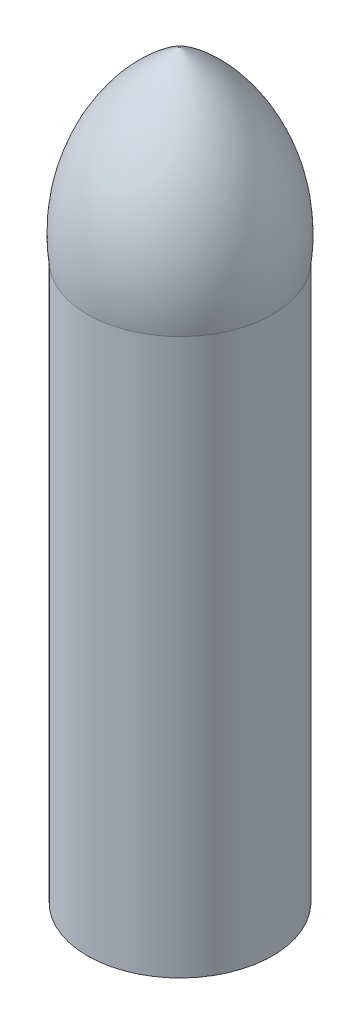
SolidWorks part; units mm, degrees
ref_plane "Front Plane" through (0, 0, 0) normal (0, 0, 1) x (1, 0, 0)
ref_plane "Top Plane" through (0, 0, 0) normal (0, 1, 0) x (1, 0, 0)
ref_plane "Right Plane" through (0, 0, 0) normal (1, 0, 0) x (0, 0, -1)
sketch "Sketch1" plane through (0, 0, 0) normal (0, 0, 1) x (1, 0, 0)
  line L0 (0, 0) -> (0, 100)
  line L1 (0, 0) -> (50, 0)
  arc A0 (0, 100) -> (50, 0) centre (-49.162, 12.919) cw
  dimension "D1" = 100
  dimension "D2" = 50
revolve "Revolve1" add sketch "Sketch1" angle 360 about L0
sketch "Sketch2" plane through (0, 0, 0) normal (0, -1, 0) x (-1, 0, 0)
  circle A0 centre (0, 0) radius 50
extrude "Boss-Extrude1" add sketch "Sketch2" along normal blind 300
sketch3d "3DSketch1"
  line L0 (0, -298.2152, -9.3836) -> (0, -200.6807, -9.3836) construction
  line L1 (0, -298.2152, -9.3836) -> (0, -298.2152, 5.6164)
  line L2 (0, -298.2152, 5.6164) -> (0, -200.6807, 5.6164)
  line L3 (0, -200.6807, 5.6164) -> (0, -200.6807, -9.3836)
  line L4 (0, -200.6807, -9.3836) -> (0, -200.6807, -24.3836)
  line L5 (0, -200.6807, -24.3836) -> (0, -299.0018, -24.3836)
  line L6 (0, -299.0018, -24.3836) -> (0, -298.2152, -9.3836)
  dimension "D1" = 15
  dimension "D2" = 15
